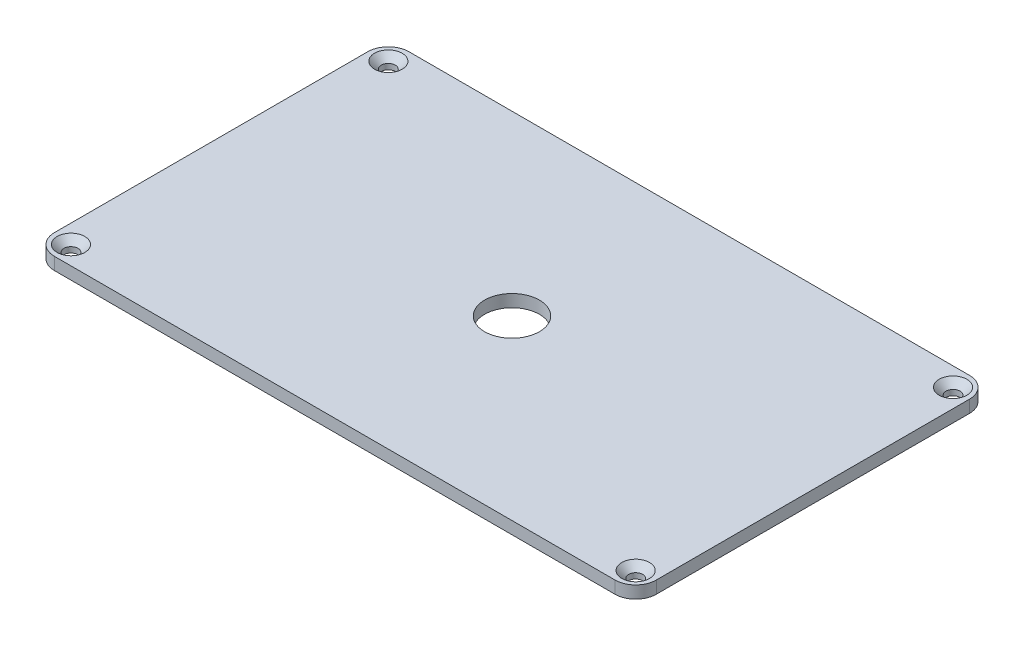
SolidWorks part; units mm, degrees
ref_plane "Front Plane" through (0, 0, 0) normal (0, 0, 1) x (1, 0, 0)
ref_plane "Top Plane" through (0, 0, 0) normal (0, 1, 0) x (1, 0, 0)
ref_plane "Right Plane" through (0, 0, 0) normal (1, 0, 0) x (0, 0, -1)
sketch "Sketch1" plane through (0, 0, 0) normal (0, 1, 0) x (1, 0, 0)
  line L0 (-62.3062, 38.2536) -> (-62.3062, -39.7464) construction
  line L1 (-66.3062, 42.2536) -> (79.6938, 42.2536)
  line L2 (-66.3062, 42.2536) -> (-66.3062, -43.7464)
  line L3 (-66.3062, -43.7464) -> (79.6938, -43.7464)
  line L4 (79.6938, 42.2536) -> (79.6938, -43.7464)
  line L5 (-62.3062, -39.7464) -> (75.6938, -39.7464) construction
  line L6 (75.6938, 38.2536) -> (75.6938, -39.7464) construction
  line L7 (-62.3062, 38.2536) -> (75.6938, 38.2536) construction
  dimension "D1" = 86
  dimension "D2" = 146
  dimension "D3" = 4
extrude "Boss-Extrude1" add sketch "Sketch1" along normal blind 3
sketch "Sketch2" plane through (0, 3, 0) normal (0, 1, 0) x (1, 0, 0)
  line L0 (79.6938, 42.2536) -> (-66.3062, 42.2536) construction
  line L1 (-66.3062, 42.2536) -> (-66.3062, -43.7464) construction
  line L2 (79.6938, -43.7464) -> (79.6938, 42.2536) construction
  point P1 (-61.8062, -39.2464)
  point P2 (-61.8062, 37.7536)
  point P3 (75.1938, 37.7536)
  point P8 (75.1938, -39.2464)
  dimension "D1" = 4.5
  dimension "D2" = 4.5
  dimension "D3" = 4.5
  dimension "D4" = 4.5
  dimension "D5" = 4.5
hole_wizard "CSK for M3 SFHCS1" positions "Sketch2" profile "Sketch3" countersink size "M3" standard "ANSI Metric" end condition through all
sketch "Sketch3" plane through (-61.8062, 3, 39.2464) normal (1, 0, 0) x (0, 0, 1)
  line L0 (0, 0) -> (0, 3)
  line L1 (0, 3) -> (1.7, 3)
  line L2 (1.7, 3) -> (1.7, 1.66)
  line L3 (1.7, 1.66) -> (3.36, 0)
  line L5 (3.36, 0) -> (0, 0)
  line L6 (-1.7, 1.66) -> (-3.36, 0) construction
  line L11 (0, -6.35) -> (0, 107.95) construction
  dimension "Thru Hole Dia." = 3.4
  dimension "Thru Hole Depth" = 3
  dimension "Near C'Sink Dia." = 6.72
  dimension "Near C'Sink Angle" = 90
sketch "Sketch5" plane through (0, 0, 0) normal (0, -1, 0) x (1, 0, 0)
  line L0 (-66.3062, 43.7464) -> (79.6938, -42.2536) construction
  circle A0 centre (6.6938, 0.7464) radius 6.65
extrude "Cut-Extrude1" cut sketch "Sketch5" against normal blind 14
sketch "Sketch6" plane through (0, 0, 0) normal (0, -1, 0) x (1, 0, 0)
  line L0 (90.9703, 0.7464) -> (-77.5827, 0.7464) construction
  line L5 (21.3588, 0.7464) -> (-27.4712, 0.7464) construction
  line L14 (-30.0562, 10.4964) -> (23.9438, 10.4964) construction
  line L15 (-30.0562, 10.4964) -> (-30.0562, -9.0036)
  line L16 (-30.0562, -9.0036) -> (23.9438, -9.0036) construction
  line L17 (23.9438, 10.4964) -> (23.9438, -9.0036)
  line L18 (-30.0562, 10.4964) -> (23.9438, -9.0036) construction
  line L19 (-30.0562, -9.0036) -> (23.9438, 10.4964) construction
  line L20 (17.0938, 10.4964) -> (-23.2062, 10.4964) construction
  line L21 (17.0938, 10.4964) -> (17.0938, -9.0036)
  line L22 (17.0938, -9.0036) -> (-23.2062, -9.0036) construction
  line L23 (-23.2062, 10.4964) -> (-23.2062, -9.0036)
  line L24 (17.0938, 10.4964) -> (-23.2062, -9.0036) construction
  line L25 (17.0938, -9.0036) -> (-23.2062, 10.4964) construction
  line L26 (-27.4712, 5.7464) -> (-27.4712, -4.2536) construction
  line L27 (21.3588, 5.7464) -> (21.3588, -4.2536) construction
  line L28 (-30.0562, 10.4964) -> (-23.2062, 10.4964)
  line L29 (-30.0562, -9.0036) -> (-23.2062, -9.0036)
  line L30 (17.0938, 10.4964) -> (23.9438, 10.4964)
  line L31 (17.0938, -9.0036) -> (23.9438, -9.0036)
  circle A0 centre (-27.4712, 5.7464) radius 1.5
  circle A1 centre (-27.4712, -4.2536) radius 1.5
  circle A2 centre (21.3588, 5.7464) radius 1.5
  circle A3 centre (21.3588, -4.2536) radius 1.5
  point P0 (-3.0562, 0.7464)
  point P3 (6.6938, 0.7464)
  point P8 (6.6938, 0.7464)
  point P9 (23.9438, 0.7464)
  point P11 (-3.0562, 0.7464)
  point P19 (-3.0562, 0.7464)
  point P22 (-27.4712, 0.7464)
  point P27 (21.3588, 0.7464)
  dimension "D2" = 54
  dimension "D1" = 17.25
  dimension "D3" = 19.5
  dimension "D4" = 40.3
  dimension "D5" = 19.5
extrude "Boss-Extrude2" add sketch "Sketch6" along normal blind 10
sketch "Sketch7" plane through (0, -10, 0) normal (0, -1, 0) x (1, 0, 0)
  line L2 (-23.2062, -9.0036) -> (-23.2062, 10.4964) construction
  line L4 (-30.2562, 1.7436) -> (-23.2062, 1.7436)
  line L5 (-30.2562, 1.7436) -> (-30.2562, -0.258)
  line L6 (-30.2562, -0.258) -> (-23.2062, -0.258)
  line L7 (-23.2062, 1.7436) -> (-23.2062, -0.258)
  line L8 (-30.2562, 1.7436) -> (-23.2062, -0.258) construction
  line L9 (-30.2562, -0.258) -> (-23.2062, 1.7436) construction
  line L11 (23.9438, -9.0036) -> (23.9438, 10.4964) construction
  line L12 (16.8938, 1.7472) -> (23.9438, 1.7472)
  line L13 (16.8938, 1.7472) -> (16.8938, -0.2544)
  line L14 (16.8938, -0.2544) -> (23.9438, -0.2544)
  line L15 (23.9438, 1.7472) -> (23.9438, -0.2544)
  line L16 (16.8938, 1.7472) -> (23.9438, -0.2544) construction
  line L17 (16.8938, -0.2544) -> (23.9438, 1.7472) construction
  point P6 (-26.7312, 0.7428)
  point P13 (20.4188, 0.7464)
extrude "Cut-Extrude2" cut sketch "Sketch7" against normal blind 3
fillet "Fillet1" radius 5 4 edges at (79.6938, 1.5, -42.2536) (79.6938, 1.5, 43.7464) (-66.3062, 1.5, 43.7464) (-66.3062, 1.5, -42.2536)
